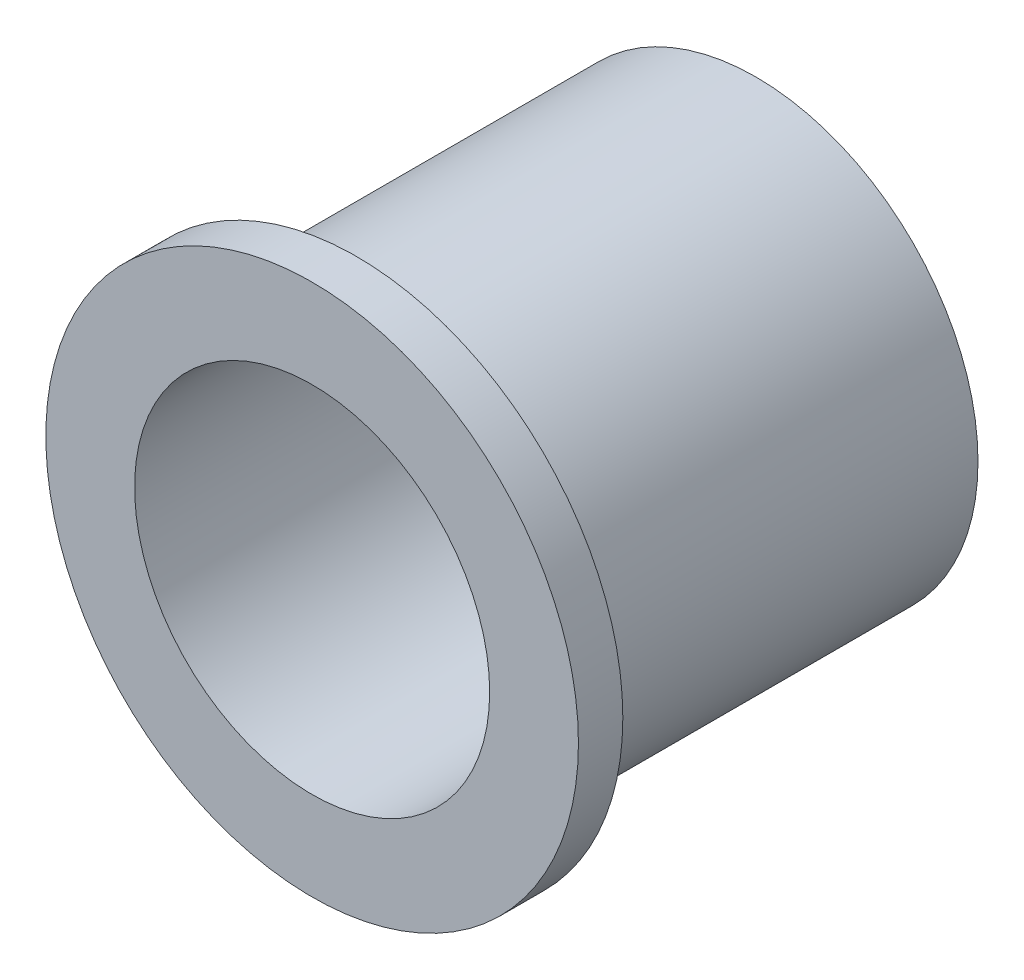
SolidWorks part; units mm, degrees
material "Manganese Bronze"
ref_plane "Front" through (0, 0, 0) normal (0, 0, 1) x (1, 0, 0)
ref_plane "Top" through (0, 0, 0) normal (0, 1, 0) x (1, 0, 0)
ref_plane "Right" through (0, 0, 0) normal (1, 0, 0) x (0, 0, -1)
sketch "Sketch1" plane through (0, 0, 0) normal (0, 0, 1) x (1, 0, 0)
  circle A0 centre (0, 0) radius 12.7 construction
  circle A1 centre (0, 0) radius 15.8813 construction
  circle A2 centre (0, 0) radius 19.05 construction
  dimension "ID" = 25.4
  dimension "OD" = 31.7627
  dimension "FlangeOD" = 38.1
sketch "Sketch2" plane through (0, 0, 0) normal (1, 0, 0) x (0, 0, -1)
  line L0 (0, 0) -> (-15.875, 0) construction
  line L1 (-15.875, 0) -> (-15.875, 19.05) construction
  line L2 (-15.875, 19.05) -> (15.875, 19.05) construction
  line L3 (15.875, 19.05) -> (15.875, 0) construction
  line L4 (15.875, 0) -> (0, 0) construction
  point P6 (0, 19.05)
  point P8 (-12.7, 0)
  dimension "Length" = 31.75
  dimension "Flange Thickness" = 3.175
sketch "Sketch3" plane through (0, 0, 0) normal (0, 0, 1) x (1, 0, 0)
  circle A0 centre (0, 0) radius 12.7 construction
  circle A1 centre (0, 0) radius 15.8813 construction
  circle A2 centre (0, 0) radius 12.7
  circle A3 centre (0, 0) radius 15.8813
extrude "Boss-Extrude1" add sketch "Sketch3" along normal up to vertex (15.875 mm away) and the other way up to vertex (15.875 mm away) up to point (0, 0, 15.875) other way up to point (0, 0, -15.875)
sketch "Sketch4" plane through (0, 0, 0) normal (0, 0, 1) x (1, 0, 0)
  circle A0 centre (0, 0) radius 12.7 construction
  circle A1 centre (0, 0) radius 19.05 construction
  circle A2 centre (0, 0) radius 12.7
  circle A3 centre (0, 0) radius 19.05
extrude "Boss-Extrude2" add sketch "Sketch4" along normal up to vertex (15.875 mm away) from vertex at 12.7 starting at point (0, 0, 12.7)
